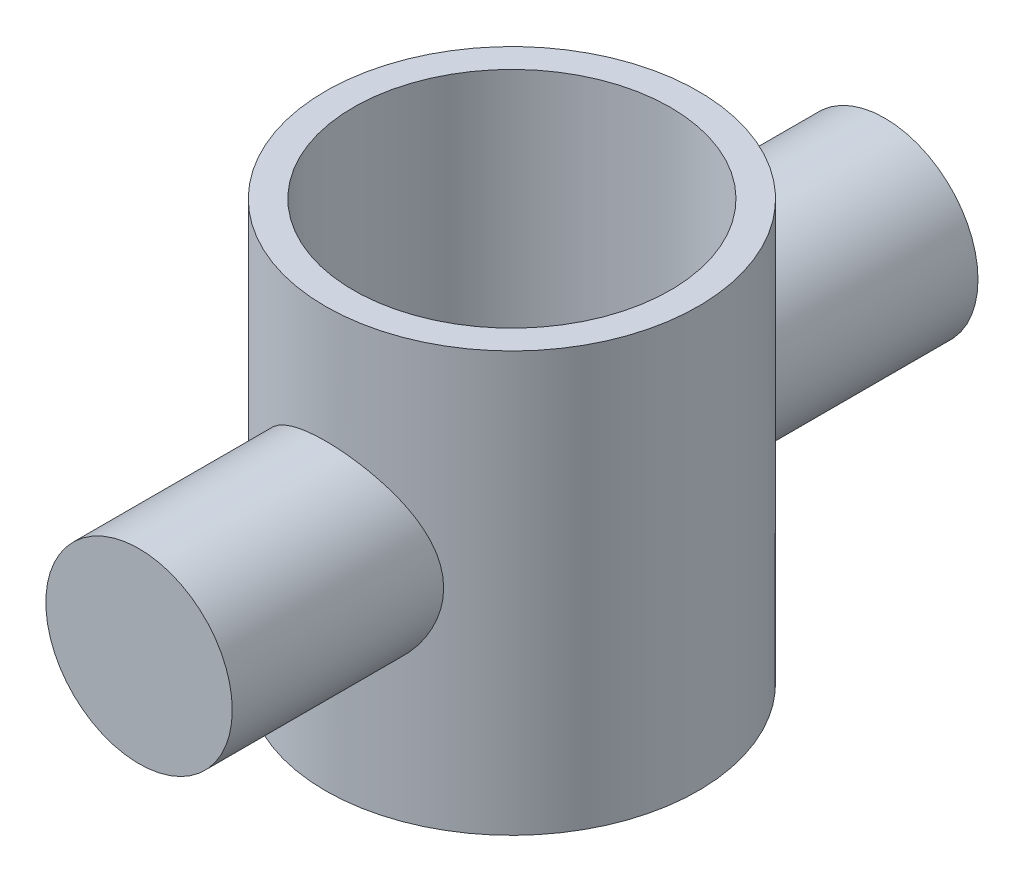
SolidWorks part; units mm, degrees
ref_plane "前视基准面" through (0, 0, 0) normal (0, 0, 1) x (1, 0, 0)
ref_plane "上视基准面" through (0, 0, 0) normal (0, 1, 0) x (1, 0, 0)
ref_plane "右视基准面" through (0, 0, 0) normal (1, 0, 0) x (0, 0, -1)
sketch "草图2" plane through (0, 0, 0) normal (0, 1, 0) x (1, 0, 0)
  circle A0 centre (0, 0) radius 17
  circle A1 centre (0, 0) radius 20
  dimension "D1" = 34
  dimension "D2" = 40
extrude "凸台-拉伸1" add sketch "草图2" along normal blind 45
ref_plane "基准面1" through (0, 0, 40) normal (0, 0, 1) x (1, 0, 0)
sketch "草图3" plane through (0, 0, 40) normal (0, 0, 1) x (1, 0, 0)
  line L0 (-37.8224, 22.5) -> (33.5726, 22.5) construction
  line L1 (0, -7.6512) -> (0, 58.9642) construction
  circle A0 centre (0, 22.5) radius 10
  dimension "D1" = 20
extrude "凸台-拉伸2" add sketch "草图3" against normal up to next
cosmetic thread "装饰螺纹线1" parameters "D1"=5, "D2"=17.252
mirror "镜向2" about plane through (0, 0, 0) normal (0, 0, 1) of "凸台-拉伸2"
